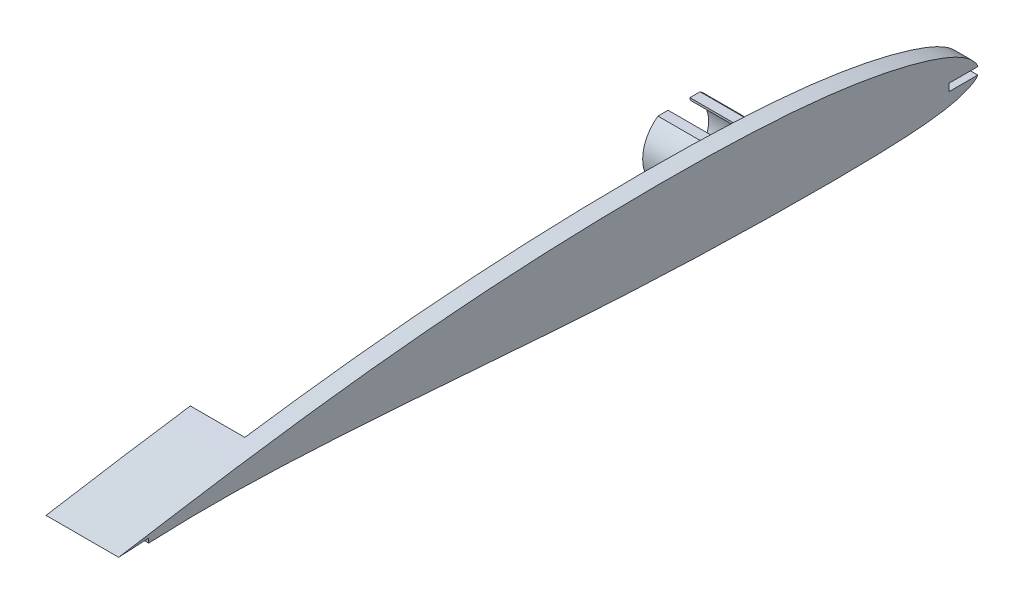
SolidWorks part; units mm, degrees
material "Manual Density from Real Component Centina"
ref_plane "Piano frontale" through (0, 0, 0) normal (0, 0, 1) x (1, 0, 0)
ref_plane "Piano superiore" through (0, 0, 0) normal (0, 1, 0) x (1, 0, 0)
ref_plane "Piano destro" through (0, 0, 0) normal (1, 0, 0) x (0, 0, -1)
curve "Curva1"
  spline degree 3 poles (0, 0.1724, 248.285) (0, -0.053, 250.4273) (0, 0.2462, 248.3284) (0, 0.5529, 246.6445) (0, 1.2459, 242.6221) (0, 2.0989, 237.7464) (0, 3.1818, 231.3634) (0, 4.2933, 223.9772) (0, 5.7312, 215.5604) (0, 7.1315, 206.3004) (0, 8.6324, 196.1631) (0, 10.1162, 185.3524) (0, 11.5493, 173.9891) (0, 12.8816, 162.1914) (0, 14.0593, 150.0724) (0, 15.0523, 137.7438) (0, 15.8256, 125.3116) (0, 16.3834, 112.8888) (0, 16.7267, 100.597) (0, 16.8648, 88.5669) (0, 16.792, 76.9314) (0, 16.4941, 65.8165) (0, 15.9609, 55.3329) (0, 15.1594, 45.573) (0, 14.0978, 36.6074) (0, 12.7884, 28.4972) (0, 11.2839, 21.2988) (0, 9.6413, 15.0749) (0, 7.9136, 9.8809) (0, 6.1182, 5.7699) (0, 4.2384, 2.7289) (0, 2.3057, 0.8126) (0, 0.7927, 0.0312) (0, -0.4105, -0.0213) (0, -1.7115, 0.4949) (0, -2.8658, 2.6253) (0, -4.0404, 5.6977) (0, -4.9287, 10.0719) (0, -5.5974, 15.6262) (0, -6.0122, 22.4122) (0, -6.265, 30.3619) (0, -6.3814, 39.3972) (0, -6.3554, 49.3987) (0, -6.2185, 60.2453) (0, -5.9476, 71.8018) (0, -5.5368, 83.9408) (0, -4.9386, 96.5461) (0, -4.1527, 109.5201) (0, -3.2196, 122.7671) (0, -2.1909, 136.1764) (0, -1.148, 149.6158) (0, -0.1602, 162.9314) (0, 0.706, 175.9537) (0, 1.3896, 188.4999) (0, 1.8332, 200.3712) (0, 1.9676, 211.3376) (0, 1.8232, 221.1842) (0, 1.4973, 229.6804) (0, 1.0741, 236.8065) (0, 0.6857, 242.1894) (0, 0.3087, 246.5181) (0, 0.1724, 248.285) (0, -0.053, 250.4273) (0, 0.2462, 248.3284) knots -0.014202 -0.006329 -0.001589 0 0.001576 0.006211 0.01368 0.023764 0.036307 0.051658 0.068045 0.086769 0.107053 0.128647 0.151303 0.174786 0.19886 0.223309 0.247929 0.272522 0.296848 0.320648 0.343669 0.365658 0.3864 0.405741 0.423561 0.439779 0.454311 0.467034 0.477831 0.486643 0.493542 0.498786 0.50271 0.50309 0.505896 0.510322 0.516831 0.525521 0.536535 0.549945 0.565696 0.583577 0.603379 0.624844 0.647727 0.671743 0.696673 0.722357 0.748609 0.77521 0.801891 0.828329 0.854175 0.879074 0.902636 0.924421 0.943939 0.960827 0.974827 0.985798 0.993671 0.998411 1 1.001576 1.006211 1.01368 periodic
sketch "Schizzo1" plane through (0, 0, 0) normal (1, 0, 0) x (0, 0, -1)
  line L0 (-250, 0) -> (0.0001, 0.0174) construction
  line L1 (0.0001, 0.0174) -> (-0.0034, 50.0174) construction
  line L2 (-62.4999, 16.3096) -> (-62.4999, -6.155) construction
  line L4 (-78.4999, 10.0773) -> (-93.4999, 10.0773) construction
  line L5 (-78.4999, 10.0773) -> (-78.4999, 0.0773) construction
  line L6 (-78.4999, 0.0773) -> (-93.4999, 0.0773) construction
  line L7 (-93.4999, 10.0773) -> (-93.4999, 0.0773) construction
  circle A0 centre (-62.4999, 5.0773) radius 8 construction
  spline S0 degree 3 poles (-248.3284, 0.2462) (-250.4273, -0.053) (-248.285, 0.1724) (-246.5181, 0.3087) (-242.1894, 0.6857) (-236.8065, 1.0741) (-229.6804, 1.4973) (-221.1842, 1.8232) (-211.3376, 1.9676) (-200.3712, 1.8332) (-188.4999, 1.3896) (-175.9537, 0.706) (-162.9314, -0.1602) (-149.6158, -1.148) (-136.1764, -2.1909) (-122.7671, -3.2196) (-109.5201, -4.1527) (-96.5461, -4.9386) (-83.9408, -5.5368) (-71.8018, -5.9476) (-60.2453, -6.2185) (-49.3987, -6.3554) (-39.3972, -6.3814) (-30.3619, -6.265) (-22.4122, -6.0122) (-15.6262, -5.5974) (-10.0719, -4.9287) (-5.6977, -4.0404) (-2.6253, -2.8658) (-0.4949, -1.7115) (0.0213, -0.4105) (-0.0312, 0.7927) (-0.8126, 2.3057) (-2.7289, 4.2384) (-5.7699, 6.1182) (-9.8809, 7.9136) (-15.0749, 9.6413) (-21.2988, 11.2839) (-28.4972, 12.7884) (-36.6074, 14.0978) (-45.573, 15.1594) (-55.3329, 15.9609) (-65.8165, 16.4941) (-76.9314, 16.792) (-88.5669, 16.8648) (-100.597, 16.7267) (-112.8888, 16.3834) (-125.3116, 15.8256) (-137.7438, 15.0523) (-150.0724, 14.0593) (-162.1914, 12.8816) (-173.9891, 11.5493) (-185.3524, 10.1162) (-196.1631, 8.6324) (-206.3004, 7.1315) (-215.5604, 5.7312) (-223.9772, 4.2933) (-231.3634, 3.1818) (-237.7464, 2.0989) (-242.6221, 1.2459) (-246.6445, 0.5529) (-248.3284, 0.2462) (-250.4273, -0.053) (-248.285, 0.1724) knots -0.01368 -0.006211 -0.001576 0 0.001589 0.006329 0.014202 0.025173 0.039173 0.056061 0.075579 0.097364 0.120926 0.145825 0.171671 0.198109 0.22479 0.251391 0.277643 0.303327 0.328257 0.352273 0.375156 0.396621 0.416423 0.434304 0.450055 0.463465 0.474479 0.483169 0.489678 0.494104 0.49691 0.49729 0.501214 0.506458 0.513357 0.522169 0.532966 0.545689 0.560221 0.576439 0.594259 0.6136 0.634342 0.656331 0.679352 0.703152 0.727478 0.752071 0.776691 0.80114 0.825214 0.848697 0.871353 0.892947 0.913231 0.931955 0.948342 0.963693 0.976236 0.98632 0.993789 0.998424 1 1.001589 1.006329 1.014202 only from (-250, 0) to (-250, 0) construction
  spline S1 degree 3 poles (-248.3284, 0.2462) (-250.4273, -0.053) (-248.285, 0.1724) (-246.5181, 0.3087) (-242.1894, 0.6857) (-236.8065, 1.0741) (-229.6804, 1.4973) (-221.1842, 1.8232) (-211.3376, 1.9676) (-200.3712, 1.8332) (-188.4999, 1.3896) (-175.9537, 0.706) (-162.9314, -0.1602) (-149.6158, -1.148) (-136.1764, -2.1909) (-122.7671, -3.2196) (-109.5201, -4.1527) (-96.5461, -4.9386) (-83.9408, -5.5368) (-71.8018, -5.9476) (-60.2453, -6.2185) (-49.3987, -6.3554) (-39.3972, -6.3814) (-30.3619, -6.265) (-22.4122, -6.0122) (-15.6262, -5.5974) (-10.0719, -4.9287) (-5.6977, -4.0404) (-2.6253, -2.8658) (-0.4949, -1.7115) (0.0213, -0.4105) (-0.0312, 0.7927) (-0.8126, 2.3057) (-2.7289, 4.2384) (-5.7699, 6.1182) (-9.8809, 7.9136) (-15.0749, 9.6413) (-21.2988, 11.2839) (-28.4972, 12.7884) (-36.6074, 14.0978) (-45.573, 15.1594) (-55.3329, 15.9609) (-65.8165, 16.4941) (-76.9314, 16.792) (-88.5669, 16.8648) (-100.597, 16.7267) (-112.8888, 16.3834) (-125.3116, 15.8256) (-137.7438, 15.0523) (-150.0724, 14.0593) (-162.1914, 12.8816) (-173.9891, 11.5493) (-185.3524, 10.1162) (-196.1631, 8.6324) (-206.3004, 7.1315) (-215.5604, 5.7312) (-223.9772, 4.2933) (-231.3634, 3.1818) (-237.7464, 2.0989) (-242.6221, 1.2459) (-246.6445, 0.5529) (-248.3284, 0.2462) (-250.4273, -0.053) (-248.285, 0.1724) knots -0.01368 -0.006211 -0.001576 0 0.001589 0.006329 0.014202 0.025173 0.039173 0.056061 0.075579 0.097364 0.120926 0.145825 0.171671 0.198109 0.22479 0.251391 0.277643 0.303327 0.328257 0.352273 0.375156 0.396621 0.416423 0.434304 0.450055 0.463465 0.474479 0.483169 0.489678 0.494104 0.49691 0.49729 0.501214 0.506458 0.513357 0.522169 0.532966 0.545689 0.560221 0.576439 0.594259 0.6136 0.634342 0.656331 0.679352 0.703152 0.727478 0.752071 0.776691 0.80114 0.825214 0.848697 0.871353 0.892947 0.913231 0.931955 0.948342 0.963693 0.976236 0.98632 0.993789 0.998424 1 1.001589 1.006329 1.014202 only from (-250, 0) to (-250, 0)
  point P11 (-78.4999, 5.0773)
  dimension "D3" = 16
  dimension "D1" = 50
  dimension "D2" = 62.5
  dimension "D4" = 15
  dimension "D5" = 10
  dimension "D6" = 16
extrude "CorpoCentina" add sketch "Schizzo1" along normal blind 5
sketch "Schizzo3" plane through (5, 0, 0) normal (1, 0, 0) x (0, 0, -1)
  line L0 (-200, 8.0593) -> (-200, 1.7757) construction
  line L1 (-200.5, 6.4175) -> (-199.5, 3.4175) construction
  line L2 (-197.4019, 6.4175) -> (-199.5, 6.4175)
  line L4 (-197.4019, 3.4175) -> (-199.5, 3.4175)
  line L7 (-200.5, 6.4175) -> (-200.5, 6.3317)
  line L9 (-199.5, 6.4175) -> (-199.5, 6.3317)
  line L10 (-199.5, 6.4175) -> (-200.5, 3.4175) construction
  line L11 (-200.5, 6.4175) -> (-202.5981, 6.4175)
  line L12 (-200.5, 3.4175) -> (-202.5981, 3.4175)
  line L13 (-199.5, 3.5033) -> (-199.5, 3.4175)
  line L14 (-200.5, 3.5033) -> (-200.5, 3.4175)
  arc A0 (-200.5, 6.3317) -> (-200.5, 3.5033) centre (-200, 4.9175) ccw
  arc A1 (-202.5981, 6.4175) -> (-202.5981, 3.4175) centre (-200, 4.9175) ccw
  arc A2 (-197.4019, 3.4175) -> (-197.4019, 6.4175) centre (-200, 4.9175) ccw
  arc A3 (-199.5, 3.5033) -> (-199.5, 6.3317) centre (-200, 4.9175) ccw
  spline S0 degree 3 poles (-248.3284, 0.2462) (-250.4273, -0.053) (-248.285, 0.1724) (-246.5181, 0.3087) (-242.1894, 0.6857) (-236.8065, 1.0741) (-229.6804, 1.4973) (-221.1842, 1.8232) (-211.3376, 1.9676) (-200.3712, 1.8332) (-188.4999, 1.3896) (-175.9537, 0.706) (-162.9314, -0.1602) (-149.6158, -1.148) (-136.1764, -2.1909) (-122.7671, -3.2196) (-109.5201, -4.1527) (-96.5461, -4.9386) (-83.9408, -5.5368) (-71.8018, -5.9476) (-60.2453, -6.2185) (-49.3987, -6.3554) (-39.3972, -6.3814) (-30.3619, -6.265) (-22.4122, -6.0122) (-15.6262, -5.5974) (-10.0719, -4.9287) (-5.6977, -4.0404) (-2.6253, -2.8658) (-0.4949, -1.7115) (0.0213, -0.4105) (-0.0312, 0.7927) (-0.8126, 2.3057) (-2.7289, 4.2384) (-5.7699, 6.1182) (-9.8809, 7.9136) (-15.0749, 9.6413) (-21.2988, 11.2839) (-28.4972, 12.7884) (-36.6074, 14.0978) (-45.573, 15.1594) (-55.3329, 15.9609) (-65.8165, 16.4941) (-76.9314, 16.792) (-88.5669, 16.8648) (-100.597, 16.7267) (-112.8888, 16.3834) (-125.3116, 15.8256) (-137.7438, 15.0523) (-150.0724, 14.0593) (-162.1914, 12.8816) (-173.9891, 11.5493) (-185.3524, 10.1162) (-196.1631, 8.6324) (-206.3004, 7.1315) (-215.5604, 5.7312) (-223.9772, 4.2933) (-231.3634, 3.1818) (-237.7464, 2.0989) (-242.6221, 1.2459) (-246.6445, 0.5529) (-248.3284, 0.2462) (-250.4273, -0.053) (-248.285, 0.1724) knots -0.01368 -0.006211 -0.001576 0 0.001589 0.006329 0.014202 0.025173 0.039173 0.056061 0.075579 0.097364 0.120926 0.145825 0.171671 0.198109 0.22479 0.251391 0.277643 0.303327 0.328257 0.352273 0.375156 0.396621 0.416423 0.434304 0.450055 0.463465 0.474479 0.483169 0.489678 0.494104 0.49691 0.49729 0.501214 0.506458 0.513357 0.522169 0.532966 0.545689 0.560221 0.576439 0.594259 0.6136 0.634342 0.656331 0.679352 0.703152 0.727478 0.752071 0.776691 0.80114 0.825214 0.848697 0.871353 0.892947 0.913231 0.931955 0.948342 0.963693 0.976236 0.98632 0.993789 0.998424 1 1.001589 1.006329 1.014202 only from (-250, 0) to (-250, 0) construction
  dimension "D1" = 3
  dimension "D2" = 6
  dimension "D3" = 50
  dimension "D4" = 1
extrude "PernoAggancioAlettone" add sketch "Schizzo3" against normal blind 20
sketch "Schizzo4" plane through (0, 0, 0) normal (-1, 0, 0) x (0, 0, 1)
  line L1 (56.7053, 13.2273) -> (59.4999, 13.2273)
  line L3 (56.7053, -3.0727) -> (59.4999, -3.0727)
  line L12 (59.4999, 13.2273) -> (65.4999, -3.0727) construction
  line L14 (59.4999, 13.2273) -> (59.4999, 12.6551)
  line L16 (65.4999, 13.2273) -> (65.4999, 12.6551)
  line L17 (65.4999, 13.2273) -> (68.2945, 13.2273)
  line L18 (65.4999, -2.5004) -> (65.4999, -3.0727)
  line L19 (59.4999, -2.5004) -> (59.4999, -3.0727)
  line L20 (65.4999, -3.0727) -> (68.2945, -3.0727)
  arc A0 (59.4999, 12.6551) -> (59.4999, -2.5004) centre (62.4999, 5.0773) ccw
  arc A1 (56.7053, 13.2273) -> (56.7053, -3.0727) centre (62.4999, 5.0773) ccw
  arc A3 (68.2945, -3.0727) -> (68.2945, 13.2273) centre (62.4999, 5.0773) ccw
  arc A4 (65.4999, -2.5004) -> (65.4999, 12.6551) centre (62.4999, 5.0773) ccw
  dimension "D1" = 20
  dimension "D2" = 8.15
  dimension "D3" = 6
extrude "AggancioLongherone" add sketch "Schizzo4" along normal blind 15
sketch "Schizzo5" plane through (0, 0, 0) normal (-1, 0, 0) x (0, 0, 1)
  line L0 (197, 8.4938) -> (197, 1.689) construction
  line L1 (197, 8.4938) -> (197.4019, 6.4175)
  line L2 (197.4019, 3.4175) -> (197, 1.689)
  line L4 (200.5, 6.4175) -> (202.5981, 6.4175) construction
  line L5 (202.5981, 3.4175) -> (200.5, 3.4175) construction
  line L6 (200.5, 3.4175) -> (200.5, 3.5033) construction
  line L7 (199.5, 3.4175) -> (199.5, 3.5033) construction
  line L8 (197.4019, 3.4175) -> (199.5, 3.4175) construction
  line L9 (197.4019, 6.4175) -> (199.5, 6.4175) construction
  line L10 (200.5, 6.3317) -> (200.5, 6.4175) construction
  line L11 (199.5, 6.4175) -> (199.5, 6.3317) construction
  line L12 (200.5, 6.3317) -> (200.5, 6.4175)
  line L13 (199.5, 6.4175) -> (199.5, 6.3317)
  line L14 (200.5, 6.4175) -> (202.5981, 6.4175)
  line L15 (202.5981, 3.4175) -> (200.5, 3.4175)
  line L16 (200.5, 3.4175) -> (200.5, 3.5033)
  line L17 (199.5, 3.4175) -> (199.5, 3.5033)
  line L18 (197.4019, 3.4175) -> (199.5, 3.4175)
  line L19 (197.4019, 6.4175) -> (199.5, 6.4175)
  arc A0 (197.4019, 6.4175) -> (197.4019, 3.4175) centre (200, 4.9175) ccw construction
  arc A1 (202.5981, 3.4175) -> (202.5981, 6.4175) centre (200, 4.9175) ccw construction
  arc A2 (202.5981, 3.4175) -> (202.5981, 6.4175) centre (200, 4.9175) ccw
  arc A3 (199.5, 6.3317) -> (200.5, 6.3317) centre (200, 4.9175) cw
  arc A4 (199.5, 3.5033) -> (200.5, 3.5033) centre (200, 4.9175) ccw
  spline S0 degree 3 poles (248.285, 0.1724) (250.4273, -0.053) (248.3284, 0.2462) (246.6445, 0.5529) (242.6221, 1.2459) (237.7464, 2.0989) (231.3634, 3.1818) (223.9772, 4.2933) (215.5604, 5.7312) (206.3004, 7.1315) (196.1631, 8.6324) (185.3524, 10.1162) (173.9891, 11.5493) (162.1914, 12.8816) (150.0724, 14.0593) (137.7438, 15.0523) (125.3116, 15.8256) (112.8888, 16.3834) (100.597, 16.7267) (88.5669, 16.8648) (76.9314, 16.792) (65.8165, 16.4941) (55.3329, 15.9609) (45.573, 15.1594) (36.6074, 14.0978) (28.4972, 12.7884) (21.2988, 11.2839) (15.0749, 9.6413) (9.8809, 7.9136) (5.7699, 6.1182) (2.7289, 4.2384) (0.8126, 2.3057) (0.0312, 0.7927) (-0.0213, -0.4105) (0.4949, -1.7115) (2.6253, -2.8658) (5.6977, -4.0404) (10.0719, -4.9287) (15.6262, -5.5974) (22.4122, -6.0122) (30.3619, -6.265) (39.3972, -6.3814) (49.3987, -6.3554) (60.2453, -6.2185) (71.8018, -5.9476) (83.9408, -5.5368) (96.5461, -4.9386) (109.5201, -4.1527) (122.7671, -3.2196) (136.1764, -2.1909) (149.6158, -1.148) (162.9314, -0.1602) (175.9537, 0.706) (188.4999, 1.3896) (200.3712, 1.8332) (211.3376, 1.9676) (221.1842, 1.8232) (229.6804, 1.4973) (236.8065, 1.0741) (242.1894, 0.6857) (246.5181, 0.3087) (248.285, 0.1724) (250.4273, -0.053) (248.3284, 0.2462) knots -0.014202 -0.006329 -0.001589 0 0.001576 0.006211 0.01368 0.023764 0.036307 0.051658 0.068045 0.086769 0.107053 0.128647 0.151303 0.174786 0.19886 0.223309 0.247929 0.272522 0.296848 0.320648 0.343669 0.365658 0.3864 0.405741 0.423561 0.439779 0.454311 0.467034 0.477831 0.486643 0.493542 0.498786 0.50271 0.50309 0.505896 0.510322 0.516831 0.525521 0.536535 0.549945 0.565696 0.583577 0.603379 0.624844 0.647727 0.671743 0.696673 0.722357 0.748609 0.77521 0.801891 0.828329 0.854175 0.879074 0.902636 0.924421 0.943939 0.960827 0.974827 0.985798 0.993671 0.998411 1 1.001576 1.006211 1.01368 only from (250, 0) to (250, 0) construction
  spline S1 degree 3 poles (197, 1.689) (198.2241, 1.728) (203.1303, 1.867) (211.3376, 1.9676) (221.1842, 1.8232) (229.6804, 1.4973) (236.8065, 1.0741) (242.1894, 0.6857) (246.5181, 0.3087) (248.285, 0.1724) (250.4273, -0.053) (248.3284, 0.2462) (246.6445, 0.5529) (242.6221, 1.2459) (237.7464, 2.0989) (231.3634, 3.1818) (223.9772, 4.2933) (215.5604, 5.7312) (206.5068, 7.1003) (200.1884, 8.0364) (197, 8.4938) knots 0.895394 0.895394 0.895394 0.895394 0.902636 0.924421 0.943939 0.960827 0.974827 0.985798 0.993671 0.998411 1 1.001576 1.006211 1.01368 1.023764 1.036307 1.051658 1.068045 1.086769 1.105818 1.105818 1.105818 1.105818
extrude "RinforzoBordoDiUscita" add sketch "Schizzo5" along normal up to surface (15 mm away) up to face at (-15, 4.9175, 198.567)
sketch "Schizzo6" plane through (0, 0, 0) normal (-1, 0, 0) x (0, 0, 1)
  line L0 (0, 0) -> (52.4999, 5.0773) construction
  line L1 (-0.0001, 1) -> (8.1999, 1)
  line L6 (-0.0001, 1) -> (-0.0001, -1)
  line L7 (-0.0001, -1) -> (8.1999, -1)
  line L8 (8.1999, 1) -> (8.1999, -1)
  arc A0 (56.7053, 13.2273) -> (56.7053, -3.0727) centre (62.4999, 5.0773) ccw construction
  spline S1 degree 3 poles (197, 1.689) (194.2419, 1.601) (187.277, 1.323) (175.9537, 0.706) (162.9314, -0.1602) (149.6158, -1.148) (136.1764, -2.1909) (122.7671, -3.2196) (109.5201, -4.1527) (96.5461, -4.9386) (83.9408, -5.5368) (71.8018, -5.9476) (60.2453, -6.2185) (49.3987, -6.3554) (39.3972, -6.3814) (30.3619, -6.265) (22.4122, -6.0122) (15.6262, -5.5974) (10.0719, -4.9287) (5.6977, -4.0404) (2.6253, -2.8658) (0.4949, -1.7115) (-0.0213, -0.4105) (0.0312, 0.7927) (0.8126, 2.3057) (2.7289, 4.2384) (5.7699, 6.1182) (9.8809, 7.9136) (15.0749, 9.6413) (21.2988, 11.2839) (28.4972, 12.7884) (36.6074, 14.0978) (45.573, 15.1594) (55.3329, 15.9609) (65.8165, 16.4941) (76.9314, 16.792) (88.5669, 16.8648) (100.597, 16.7267) (112.8888, 16.3834) (125.3116, 15.8256) (137.7438, 15.0523) (150.0724, 14.0593) (162.1914, 12.8816) (173.9891, 11.5493) (185.3524, 10.1162) (192.972, 9.0704) (196.7933, 8.5234) (197, 8.4938) knots 0.104606 0.104606 0.104606 0.104606 0.120926 0.145825 0.171671 0.198109 0.22479 0.251391 0.277643 0.303327 0.328257 0.352273 0.375156 0.396621 0.416423 0.434304 0.450055 0.463465 0.474479 0.483169 0.489678 0.494104 0.49691 0.49729 0.501214 0.506458 0.513357 0.522169 0.532966 0.545689 0.560221 0.576439 0.594259 0.6136 0.634342 0.656331 0.679352 0.703152 0.727478 0.752071 0.776691 0.80114 0.825214 0.848697 0.871353 0.892947 0.894182 0.894182 0.894182 0.894182 construction
  point P13 (-0.0001, 0)
  dimension "D1" = 2
  dimension "D2" = 8.2
extrude "IntaglioAnteriore" cut sketch "Schizzo6" against normal through all
sketch "Schizzo7" plane through (-15, 0, 0) normal (-1, 0, 0) x (0, 0, 1)
  line L0 (228.544, 2.7244) -> (228.4772, 1.5262)
  line L1 (228.4772, 1.5262) -> (236.6645, 1.07)
  line L2 (236.6645, 1.07) -> (236.7313, 2.2681)
  line L3 (236.7313, 2.2681) -> (228.544, 2.7244)
  line L4 (236.9859, 6.8368) -> (236.2101, -7.0863)
  line L5 (236.2101, -7.0863) -> (260.3029, -8.4288)
  line L6 (260.3029, -8.4288) -> (261.0788, 5.4943)
  line L7 (261.0788, 5.4943) -> (236.9859, 6.8368)
  spline S0 degree 3 poles (197, 8.4938) (200.1884, 8.0364) (206.5068, 7.1003) (215.5604, 5.7312) (223.9772, 4.2933) (231.3634, 3.1818) (237.7464, 2.0989) (242.6221, 1.2459) (246.6445, 0.5529) (248.3284, 0.2462) (250.4273, -0.053) (248.285, 0.1724) (246.5181, 0.3087) (242.1894, 0.6857) (236.8065, 1.0741) (229.6804, 1.4973) (221.1842, 1.8232) (211.3376, 1.9676) (203.1303, 1.867) (198.2241, 1.728) (197, 1.689) knots 0.894182 0.894182 0.894182 0.894182 0.913231 0.931955 0.948342 0.963693 0.976236 0.98632 0.993789 0.998424 1 1.001589 1.006329 1.014202 1.025173 1.039173 1.056061 1.075579 1.097364 1.104606 1.104606 1.104606 1.104606 construction
  spline M12 degree 3 poles (248.285, 0.1724) (250.4273, -0.053) (248.3284, 0.2462) (246.6445, 0.5529) (242.6221, 1.2459) (237.7464, 2.0989) (231.3634, 3.1818) (223.9772, 4.2933) (215.5604, 5.7312) (206.3004, 7.1315) (196.1631, 8.6324) (185.3524, 10.1162) (173.9891, 11.5493) (162.1914, 12.8816) (150.0724, 14.0593) (137.7438, 15.0523) (125.3116, 15.8256) (112.8888, 16.3834) (100.597, 16.7267) (88.5669, 16.8648) (76.9314, 16.792) (65.8165, 16.4941) (55.3329, 15.9609) (45.573, 15.1594) (36.6074, 14.0978) (28.4972, 12.7884) (21.2988, 11.2839) (15.0749, 9.6413) (9.8809, 7.9136) (5.7699, 6.1182) (2.7289, 4.2384) (0.8126, 2.3057) (0.0312, 0.7927) (-0.0213, -0.4105) (0.4949, -1.7115) (2.6253, -2.8658) (5.6977, -4.0404) (10.0719, -4.9287) (15.6262, -5.5974) (22.4122, -6.0122) (30.3619, -6.265) (39.3972, -6.3814) (49.3987, -6.3554) (60.2453, -6.2185) (71.8018, -5.9476) (83.9408, -5.5368) (96.5461, -4.9386) (109.5201, -4.1527) (122.7671, -3.2196) (136.1764, -2.1909) (149.6158, -1.148) (162.9314, -0.1602) (175.9537, 0.706) (188.4999, 1.3896) (200.3712, 1.8332) (211.3376, 1.9676) (221.1842, 1.8232) (229.6804, 1.4973) (236.8065, 1.0741) (242.1894, 0.6857) (246.5181, 0.3087) (248.285, 0.1724) (250.4273, -0.053) (248.3284, 0.2462) knots -0.014202 -0.006329 -0.001589 0 0.001576 0.006211 0.01368 0.023764 0.036307 0.051658 0.068045 0.086769 0.107053 0.128647 0.151303 0.174786 0.19886 0.223309 0.247929 0.272522 0.296848 0.320648 0.343669 0.365658 0.3864 0.405741 0.423561 0.439779 0.454311 0.467034 0.477831 0.486643 0.493542 0.498786 0.50271 0.50309 0.505896 0.510322 0.516831 0.525521 0.536535 0.549945 0.565696 0.583577 0.603379 0.624844 0.647727 0.671743 0.696673 0.722357 0.748609 0.77521 0.801891 0.828329 0.854175 0.879074 0.902636 0.924421 0.943939 0.960827 0.974827 0.985798 0.993671 0.998411 1 1.001576 1.006211 1.01368 only from (197, 1.689) to (197, 8.4938)
  dimension "D1" = 1.2
  dimension "D2" = 8.2
  dimension "D3" = 13.9231
  dimension "D4" = 24.0929
  dimension "D5" = 9.3903
extrude "IntaglioPosteriore" cut sketch "Schizzo7" against normal through all contours L6 L7 L4 L5 M12 | L2 M12
